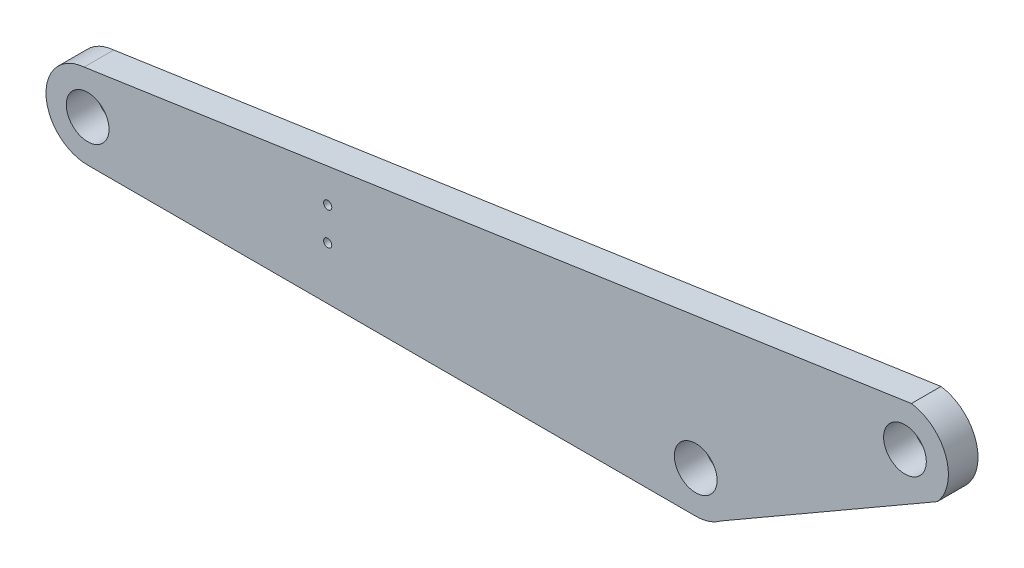
SolidWorks part; units mm, degrees
ref_plane "Plan de face" through (0, 0, 0) normal (0, 0, 1) x (1, 0, 0)
ref_plane "Plan de dessus" through (0, 0, 0) normal (0, 1, 0) x (1, 0, 0)
ref_plane "Plan de droite" through (0, 0, 0) normal (1, 0, 0) x (0, 0, -1)
sketch "Esquisse1" plane through (0, 0, 0) normal (0, 0, 1) x (1, 0, 0)
  line L0 (-370, 0) -> (0, 0) construction
  line L1 (0, 0) -> (127.3057, 73.5) construction
  line L11 (127.3057, 73.5) -> (-370, 0) construction
  line L15 (131.2507, 99.6547) -> (-372.1431, 25.2549)
  line L17 (15.2622, -20.2422) -> (146.9506, 55.7881)
  line L19 (-0.588, -25.3444) -> (-369.7411, -25.3444)
  line L21 (-223.9595, -988.0072) -> (-223.9595, 49011.9928) construction
  circle A0 centre (-370, 0) radius 13 construction
  circle A1 centre (0, 0) radius 13 construction
  circle A2 centre (127.3057, 73.5) radius 13 construction
  circle A3 centre (0, 0) radius 28.5 construction
  circle A4 centre (127.3057, 73.5) radius 28.5 construction
  circle A5 centre (-370, 0) radius 28.5 construction
  arc A6 (146.9506, 55.7881) -> (131.2507, 99.6547) centre (127.3057, 73.5) ccw
  arc A7 (-372.1431, 25.2549) -> (-369.7411, -25.3444) centre (-370, 0) ccw
  arc A8 (-0.588, -25.3444) -> (15.2622, -20.2422) centre (0, 0) ccw
  circle A9 centre (-370, 0) radius 13
  circle A10 centre (127.3057, 73.5) radius 13
  circle A11 centre (0, 0) radius 13
  circle A13 centre (-223.9595, 6.6556) radius 2.5
  circle A14 centre (-223.9595, 26.6556) radius 2.5
  dimension "D4" = 26
  dimension "D5" = 26
  dimension "D6" = 26
  dimension "D7" = 57
  dimension "D8" = 57
  dimension "D9" = 57
  dimension "D10" = 5
  dimension "D12" = 20
  dimension "D13" = 32
  dimension "D11" = 5
  dimension "D1" = 370
  dimension "D2" = 147
  dimension "D3" = 150
extrude "Boss.-Extru.1" add sketch "Esquisse1" along normal blind 18
